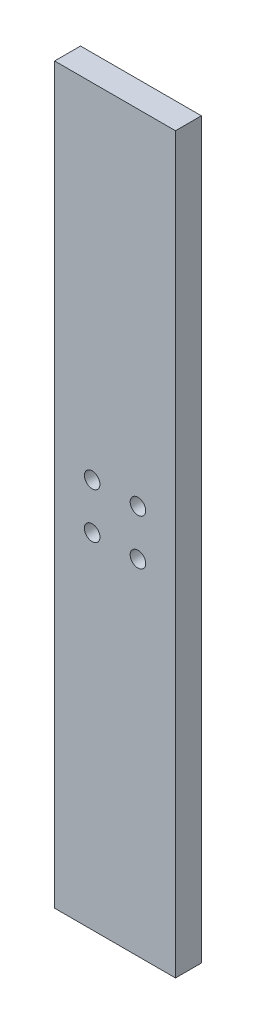
SolidWorks part; units mm, degrees
ref_plane "Front Plane" through (0, 0, 0) normal (0, 0, 1) x (1, 0, 0)
ref_plane "Top Plane" through (0, 0, 0) normal (0, 1, 0) x (1, 0, 0)
ref_plane "Right Plane" through (0, 0, 0) normal (1, 0, 0) x (0, 0, -1)
sketch "Sketch1" plane through (0, 0, 0) normal (0, 0, 1) x (1, 0, 0)
  line L1 (-7, 42.5) -> (7, 42.5)
  line L2 (-7, 42.5) -> (-7, -42.5)
  line L3 (-7, -42.5) -> (7, -42.5)
  line L4 (0, 0) -> (4.9497, -4.9497) construction
  line L5 (7, 42.5) -> (7, -42.5)
  line L6 (-7, 42.5) -> (7, -42.5) construction
  line L7 (-7, -42.5) -> (7, 42.5) construction
  circle A0 centre (0, 0) radius 7
  circle A6 centre (2.6517, -2.6517) radius 0.9
  circle A7 centre (-2.6517, -2.6517) radius 0.9
  circle A8 centre (-2.6517, 2.6517) radius 0.9
  circle A9 centre (2.6517, 2.6517) radius 0.9
  point P15 (0, 0)
  point P20 (0, 0)
  dimension "D1" = 3.25
  dimension "D2" = 4
  dimension "D3" = 85
extrude "Boss-Extrude1" add sketch "Sketch1" along normal blind 3
